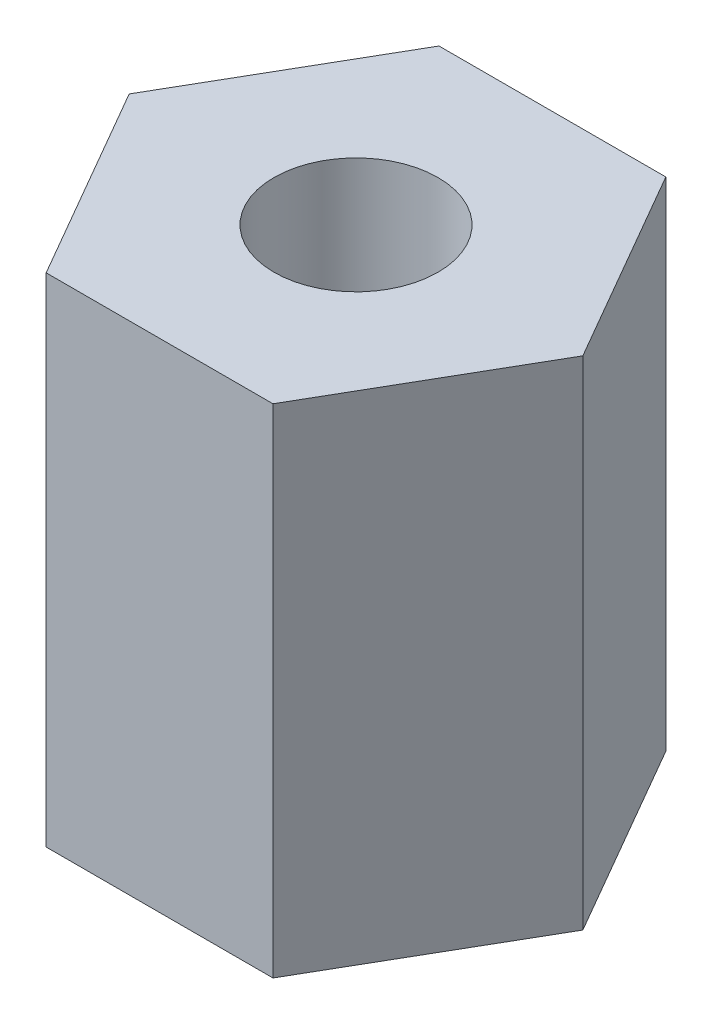
SolidWorks part; units mm, degrees
ref_plane "Front Plane" through (0, 0, 0) normal (0, 0, 1) x (1, 0, 0)
ref_plane "Top Plane" through (0, 0, 0) normal (0, 1, 0) x (1, 0, 0)
ref_plane "Right Plane" through (0, 0, 0) normal (1, 0, 0) x (0, 0, -1)
sketch "Sketch1" plane through (0, 0, 0) normal (0, 1, 0) x (1, 0, 0)
  line L1 (4.5611, 0) -> (2.2805, 3.95)
  line L2 (2.2805, 3.95) -> (-2.2805, 3.95)
  line L3 (-2.2805, 3.95) -> (-4.5611, 0)
  line L4 (-4.5611, 0) -> (-2.2805, -3.95)
  line L5 (-2.2805, -3.95) -> (2.2805, -3.95)
  line L6 (2.2805, -3.95) -> (4.5611, 0)
  circle A0 centre (0, 0) radius 3.95 construction
extrude "Boss-Extrude1" add sketch "Sketch1" along normal blind 10
sketch "Sketch9" plane through (0, 10, 0) normal (0, 1, 0) x (1, 0, 0)
  line L1 (-1.2176, -1.1136) -> (1.2176, -1.1136)
  arc A0 (-1.2176, -1.1136) -> (1.2176, -1.1136) centre (0, 0) cw
extrude "Cut-Extrude6" cut sketch "Sketch9" against normal blind 14
sketch "Sketch11" plane through (0, 10, 0) normal (0, 1, 0) x (1, 0, 0)
  circle A0 centre (0, 0) radius 1.65
extrude "Cut-Extrude7" cut sketch "Sketch11" against normal blind 3
